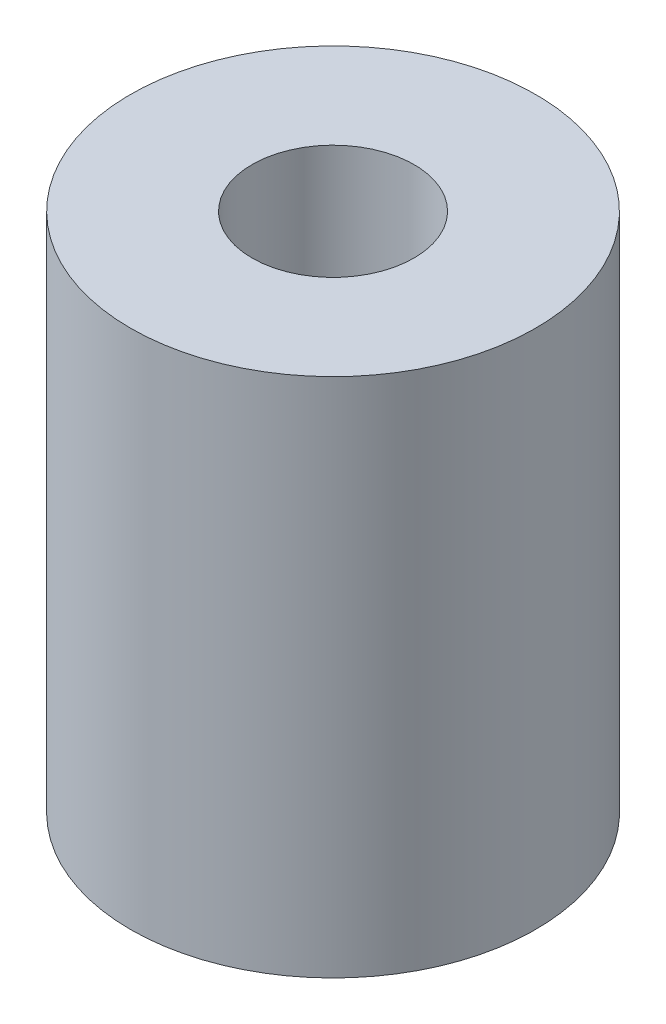
SolidWorks part; units mm, degrees
ref_plane "Alzado" through (0, 0, 0) normal (0, 0, 1) x (1, 0, 0)
ref_plane "Planta" through (0, 0, 0) normal (0, 1, 0) x (1, 0, 0)
ref_plane "Vista lateral" through (0, 0, 0) normal (1, 0, 0) x (0, 0, -1)
sketch "Croquis1" plane through (0, 0, 0) normal (0, 1, 0) x (1, 0, 0)
  circle A0 centre (0, 0) radius 3.5
  dimension "D1" = 7
extrude "Saliente-Extruir1" add sketch "Croquis1" along normal blind 9
sketch "Croquis2" plane through (0, 9, 0) normal (0, 1, 0) x (1, 0, 0)
  circle A0 centre (0, 0) radius 1.4
  dimension "D1" = 2.8
extrude "Cortar-Extruir1" cut sketch "Croquis2" against normal through all
